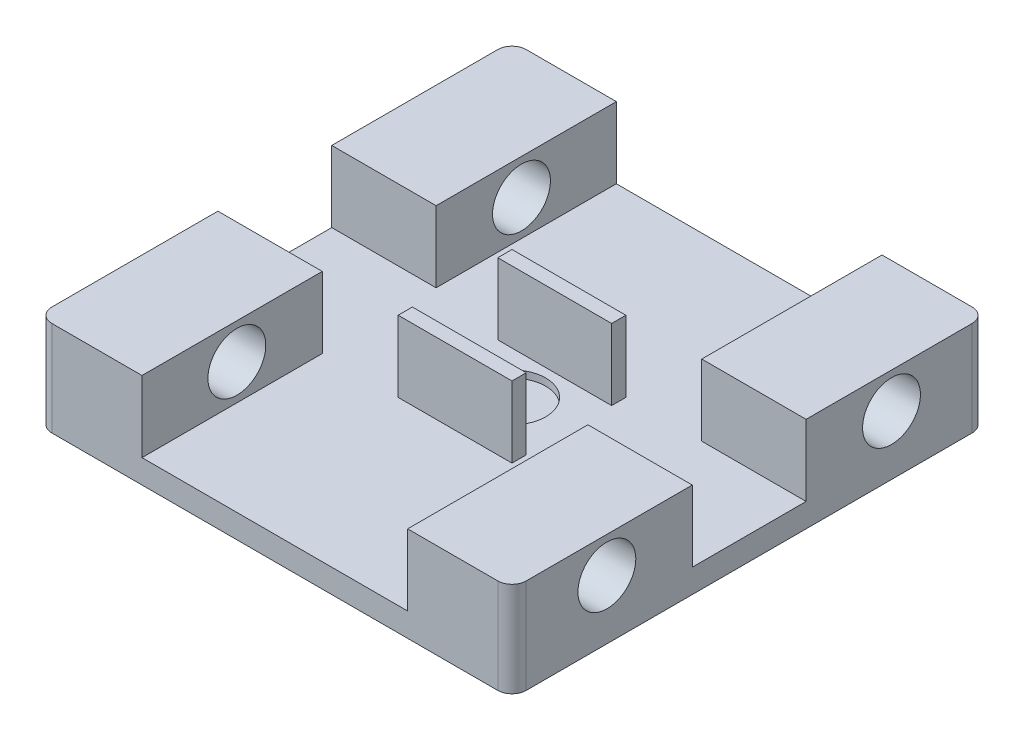
SolidWorks part; units mm, degrees
ref_plane "Front" through (0, 0, 0) normal (0, 0, 1) x (1, 0, 0)
ref_plane "Top" through (0, 0, 0) normal (0, 1, 0) x (1, 0, 0)
ref_plane "Right" through (0, 0, 0) normal (1, 0, 0) x (0, 0, -1)
sketch "Sketch1" plane through (0, 0, 0) normal (0, 1, 0) x (1, 0, 0)
  line L1 (-50, -50) -> (50, -50)
  line L2 (-50, -50) -> (-50, 50)
  line L3 (-50, 50) -> (50, 50)
  line L4 (50, -50) -> (50, 50)
  line L5 (-50, -50) -> (50, 50) construction
  line L6 (-50, 50) -> (50, -50) construction
  point P0 (0, 0)
  dimension "D1" = 100
  dimension "D2" = 100
extrude "Boss-Extrude1" add sketch "Sketch1" along normal blind 20
sketch "Sketch3" plane through (0, 20, 0) normal (0, 1, 0) x (1, 0, 0)
  circle A0 centre (0, 0) radius 7.1
extrude "Cut-Extrude1" cut sketch "Sketch3" against normal blind 16.5
sketch "Sketch4" plane through (0, 20, 0) normal (0, 1, 0) x (1, 0, 0)
  circle A0 centre (0, 0) radius 1.5
sketch "Sketch6" plane through (0, 0, 0) normal (1, 0, 0) x (0, 0, -1)
  line L3 (-7.1, 3.5) -> (7.1, 3.5)
  line L4 (-7.1, 3.5) -> (-7.1, 16.5)
  line L5 (-7.1, 16.5) -> (7.1, 16.5)
  line L6 (7.1, 3.5) -> (7.1, 16.5)
  line L7 (-7.1, 3.5) -> (7.1, 16.5) construction
  line L8 (-7.1, 16.5) -> (7.1, 3.5) construction
  point P0 (0, 0)
  point P5 (0, 10)
  dimension "D1" = 14.2
  dimension "D2" = 13
sketch "Sketch7" plane through (0, 0, 0) normal (1, 0, 0) x (0, 0, -1)
  line L0 (0, 50) -> (0, -50) construction
  circle A0 centre (30, 12.5) radius 6.1
  circle A1 centre (-30, 12.5) radius 6.1
  dimension "D3" = 12.2
extrude "Cut-Extrude4" cut sketch "Sketch7" against normal through all and the other way through all
fillet "Fillet1" radius 3 4 edges at (-50, 10, -50) (-50, 10, 50) (50, 10, 50) (50, 10, -50)
sketch "Sketch9" plane through (0, 20, 0) normal (0, 1, 0) x (1, 0, 0)
  circle A0 centre (44, -44) radius 1
sketch "Sketch10" plane through (0, 0, 0) normal (0, -1, 0) x (1, 0, 0)
  line L0 (0, -50) -> (0, 50) construction
  line L1 (28, -50) -> (-28, -50)
  line L2 (28, -50) -> (28, -12)
  line L3 (12, -12) -> (-12, -12)
  line L4 (-28, -50) -> (-28, -12)
  line L5 (28, -50) -> (-28, -12) construction
  line L6 (28, -12) -> (-28, -50) construction
  line L7 (-50, -47) -> (-50, 47) construction
  line L8 (50, 47) -> (50, -47) construction
  line L9 (47, -50) -> (-47, -50) construction
  line L10 (-47, 50) -> (47, 50) construction
  line L12 (12, -12) -> (12, 12)
  line L13 (12, 12) -> (-12, 12)
  line L14 (-12, -12) -> (-12, 12)
  line L15 (12, -12) -> (-12, 12) construction
  line L16 (12, 12) -> (-12, -12) construction
  line L18 (28, 12) -> (28, 50)
  line L19 (28, 50) -> (-28, 50)
  line L20 (-28, 12) -> (-28, 50)
  line L21 (28, 12) -> (-28, 50) construction
  line L22 (28, 50) -> (-28, 12) construction
  line L24 (-28, -12) -> (-50, -12)
  line L26 (-28, 12) -> (-50, 12)
  line L27 (-50, -12) -> (-50, 12)
  line L28 (-29.679, -10.1683) -> (-50, 12) construction
  line L29 (-28, 12) -> (-50, -12) construction
  line L30 (50, -12) -> (28, -12)
  line L31 (50, -12) -> (50, 12)
  line L32 (50, 12) -> (28, 12)
  line L34 (50, -12) -> (28, 12) construction
  line L35 (50, 12) -> (28, -12) construction
  point P0 (0, -31)
  point P13 (0, 0)
  point P19 (0, 31)
  point P26 (-39, 0)
  point P31 (39, 0)
  dimension "D1" = 22
  dimension "D2" = 22
  dimension "D3" = 0
  dimension "D4" = 24
  dimension "D5" = 24
  dimension "D7" = 22
  dimension "D8" = 22
  dimension "D10" = 0
  dimension "D11" = 0
  dimension "D13" = 0
  dimension "D15" = 0
  dimension "D17" = 0
sketch "Sketch11" plane through (0, 20, 0) normal (0, 1, 0) x (1, 0, 0)
  line L0 (50, -47) -> (50, 47) construction
  line L1 (-50, 12) -> (-28, 12)
  line L2 (-50, 12) -> (-50, -12)
  line L3 (-50, -12) -> (-28, -12)
  line L4 (50, 12) -> (50, -12)
  line L5 (-50, 12) -> (50, -12) construction
  line L6 (-50, -12) -> (50, 12) construction
  line L7 (47, 50) -> (-47, 50) construction
  line L8 (-47, -50) -> (47, -50) construction
  line L9 (12, 12) -> (-12, 12)
  line L10 (12, 12) -> (12, -12)
  line L11 (12, -12) -> (-12, -12)
  line L12 (-12, 12) -> (-12, -12)
  line L13 (12, 12) -> (-12, -12) construction
  line L14 (12, -12) -> (-12, 12) construction
  line L16 (28, -12) -> (28, -50)
  line L17 (28, -50) -> (-28, -50)
  line L18 (-28, -12) -> (-28, -50)
  line L19 (28, -12) -> (-28, -50) construction
  line L20 (28, -50) -> (-28, -12) construction
  line L21 (-50, 47) -> (-50, -47) construction
  line L22 (28, 12) -> (50, 12)
  line L23 (28, 50) -> (-28, 50)
  line L24 (28, 50) -> (28, 12)
  line L26 (-28, 50) -> (-28, 12)
  line L27 (28, 50) -> (-28, 12) construction
  line L28 (28, 12) -> (-28, 50) construction
  line L29 (28, -12) -> (50, -12)
  point P0 (0, 0)
  point P10 (0, 0)
  point P15 (0, -31)
  point P24 (0, 31)
  dimension "D1" = 38
  dimension "D2" = 24
  dimension "D4" = 22
  dimension "D5" = 22
  dimension "D6" = 0
  dimension "D7" = 22
  dimension "D8" = 22
extrude "Cut-Extrude6" cut sketch "Sketch11" against normal blind 15
sketch "Sketch12" plane through (12, 0, 0) normal (1, 0, 0) x (0, 0, -1)
  line L0 (-12, 5) -> (12, 5) construction
  line L1 (9, 20) -> (-9, 20)
  line L2 (9, 20) -> (9, 5)
  line L3 (9, 5) -> (-9, 5)
  line L4 (-9, 20) -> (-9, 5)
  line L5 (9, 20) -> (-9, 5) construction
  line L6 (9, 5) -> (-9, 20) construction
  line L7 (-12, 20) -> (12, 20) construction
  line L8 (12, 5) -> (12, 20) construction
  line L9 (-12, 5) -> (-12, 20) construction
  point P0 (0, 12.5)
  dimension "D1" = 0
  dimension "D2" = 0
  dimension "D3" = 3
  dimension "D4" = 3
extrude "Cut-Extrude7" cut sketch "Sketch12" against normal blind 32
